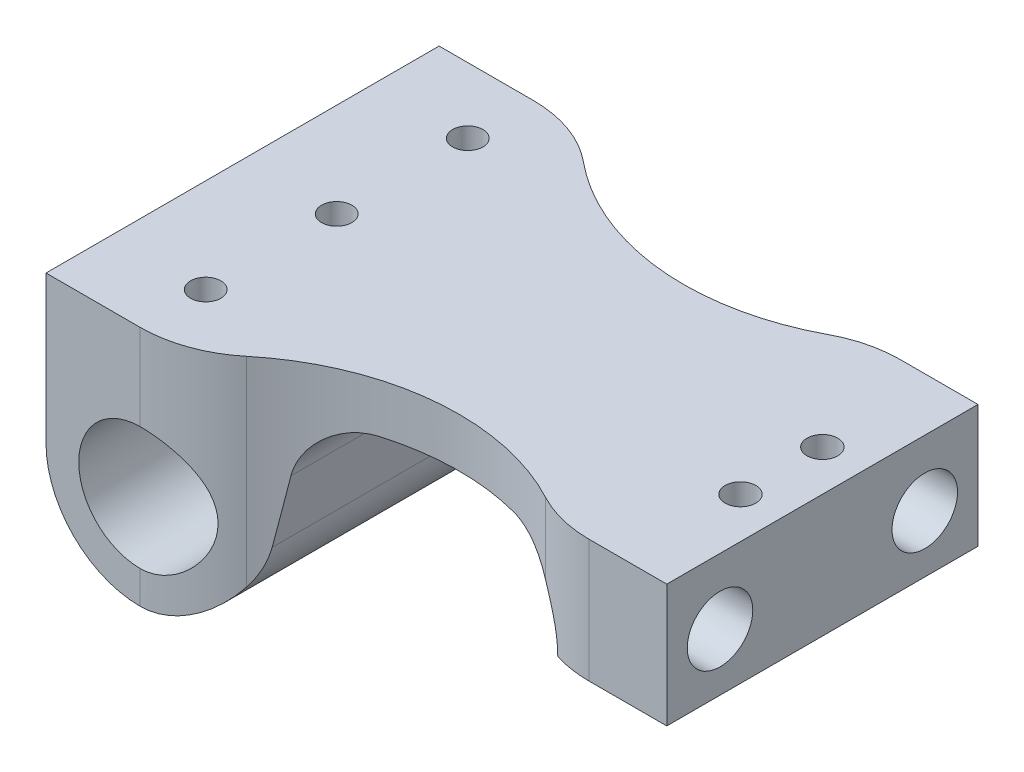
SolidWorks part; units mm, degrees
ref_plane "Front Plane" through (0, 0, 0) normal (0, 0, 1) x (1, 0, 0)
ref_plane "Top Plane" through (0, 0, 0) normal (0, 1, 0) x (1, 0, 0)
ref_plane "Right Plane" through (0, 0, 0) normal (1, 0, 0) x (0, 0, -1)
sketch "Sketch1" plane through (0, 0, 0) normal (0, 0, 1) x (1, 0, 0)
  line L0 (-17.4747, 5.003) -> (-16.0995, 12.8024)
  line L1 (10, -10) -> (-10, -10) construction
  line L2 (10, -10) -> (10, 10) construction
  line L3 (10, 10) -> (-10, 10) construction
  line L4 (-10, -10) -> (-10, 10) construction
  line L5 (10, -10) -> (-10, 10) construction
  line L6 (10, 10) -> (-10, -10) construction
  line L7 (10, 10) -> (20, 10) construction
  line L8 (10, 10) -> (10, -10) construction
  line L9 (10, -10) -> (20, -10) construction
  line L10 (20, 10) -> (20, -10) construction
  line L11 (-10, 10) -> (10, 10) construction
  line L12 (-10, 10) -> (-10, 19) construction
  line L13 (-10, 19) -> (10, 19) construction
  line L14 (10, 10) -> (10, 19) construction
  line L15 (-10, 10) -> (10, 10) construction
  line L16 (-10, 10) -> (-10, 15) construction
  line L17 (-10, 15) -> (10, 15) construction
  line L18 (10, 10) -> (10, 15) construction
  line L19 (16.5, 14.5) -> (36.5, 14.5) construction
  line L20 (16.5, 14.5) -> (16.5, 10) construction
  line L21 (25, -0.5) -> (36.5, -0.5) construction
  line L22 (36.5, 14.5) -> (36.5, -0.5) construction
  line L23 (-40.3, 25) -> (12.6275, 25)
  line L24 (-40.3, 25) -> (-40.3, 7)
  line L25 (-8.7134, 19) -> (7.5, 19)
  line L28 (25, 10) -> (25, 25)
  line L29 (25, 25) -> (12.6275, 25)
  line L30 (16.5, 10) -> (25, 10)
  line L31 (-10, 15) -> (-15, 15) construction
  line L32 (-10, 15) -> (-10, -4.1558) construction
  line L33 (-10, -4.1558) -> (-15, -4.1558) construction
  line L34 (-15, 15) -> (-15, -4.1558) construction
  circle A0 centre (-28.8, 7) radius 7.5
  arc A1 (-40.3, 7) -> (-17.4747, 5.003) centre (-28.8, 7) ccw
  arc A2 (-16.0995, 12.8024) -> (-8.7134, 19) centre (-8.7134, 11.5) cw
  arc A3 (7.5, 19) -> (16.5, 10) centre (7.5, 10) cw
  point P3 (0, 0)
  dimension "D1" = 15
  dimension "D2" = 4
  dimension "D5" = 18.8
  dimension "D6" = 3
  dimension "D10" = 6.5
  dimension "D13" = 7.5
  dimension "D3" = 20
  dimension "D4" = 20
  dimension "D7" = 10
  dimension "D8" = 9
  dimension "D9" = 5
  dimension "D11" = 20
  dimension "D12" = 6
  dimension "D14" = 80
  dimension "D15" = 5
  dimension "D16" = 5
extrude "Boss-Extrude1" add sketch "Sketch1" along normal mid plane 48
sketch "Sketch2" plane through (25, 0, 0) normal (1, 0, 0) x (0, 0, -1)
  line L0 (-12.5, 17) -> (0, 0) construction
  line L1 (0, 0) -> (12.5, 17) construction
  line L3 (-24, 25) -> (24, 25) construction
  circle A0 centre (-12.5, 17) radius 4
  circle A1 centre (12.5, 17) radius 4
  dimension "D1" = 8
  dimension "D2" = 25
  dimension "D3" = 8
extrude "Cut-Extrude1" cut sketch "Sketch2" against normal blind 5
sketch "Sketch3" plane through (0, 25, 0) normal (0, 1, 0) x (1, 0, 0)
  line L0 (25, -24) -> (-40.3, -24) construction
  line L1 (-28.8, -24) -> (25, -24)
  line L2 (25, -24) -> (25, -19)
  line L3 (21, -19) -> (25, -19)
  line L4 (25, -24) -> (25, 24) construction
  line L5 (-36.3, -24) -> (-21.3, -24) construction
  line L6 (0, 0) -> (25, 0) construction
  line L7 (21, 19) -> (25, 19)
  line L8 (25, 24) -> (25, 19)
  line L9 (-28.8, 24) -> (25, 24)
  arc A0 (-19.2546, -20.5709) -> (13.9454, -17.2375) centre (-0.1638, -43.7126) cw
  arc A1 (-28.8, -24) -> (-19.2546, -20.5709) centre (-28.8, -9) ccw
  arc A2 (13.9454, -17.2375) -> (21, -19) centre (21, -4) ccw
  arc A3 (13.9454, 17.2375) -> (21, 19) centre (21, 4) cw
  arc A4 (-28.8, 24) -> (-19.2546, 20.5709) centre (-28.8, 9) cw
  arc A5 (-19.2546, 20.5709) -> (13.9454, 17.2375) centre (-0.1638, 43.7126) ccw
  dimension "D2" = 15
  dimension "D3" = 30
  dimension "D4" = 15
  dimension "D1" = 5
  dimension "D5" = 4
extrude "Cut-Extrude2" cut sketch "Sketch3" against normal through all both and the other way through all
sketch "Sketch4" plane through (25, 0, 0) normal (1, 0, 0) x (0, 0, -1)
  line L1 (-19, 25) -> (19, 25)
  line L2 (-19, 25) -> (-19, 10)
  line L3 (-19, 10) -> (19, 10)
  line L4 (19, 25) -> (19, 10)
  circle A0 centre (12.5, 17) radius 4 construction
  circle A1 centre (-12.5, 17) radius 4 construction
  circle A2 centre (12.5, 17) radius 4
  circle A3 centre (-12.5, 17) radius 4
extrude "Boss-Extrude2" add sketch "Sketch4" along normal blind 5.5
sketch "Sketch5" plane through (0, 25, 0) normal (0, 1, 0) x (1, 0, 0)
  line L0 (30.5, 19) -> (25.5, 5) construction
  line L1 (25.5, 5) -> (25.5, -5) construction
  line L2 (25.5, -5) -> (30.5, -19) construction
  line L3 (30.5, 19) -> (30.5, -19) construction
  circle A0 centre (25.5, -5) radius 1.875
  circle A1 centre (25.5, 5) radius 1.875
  dimension "D1" = 3.75
  dimension "D2" = 3.75
  dimension "D3" = 10
  dimension "D4" = 5
extrude "Cut-Extrude3" cut sketch "Sketch5" against normal through all both and the other way through all
sketch "Sketch6" plane through (0, 25, 0) normal (0, 1, 0) x (1, 0, 0)
  line L0 (-28.8, -24) -> (-28.8, 24) construction
  line L1 (-28.8, 16) -> (-40.3, 24) construction
  line L2 (-40.3, 24) -> (-40.3, -24) construction
  line L3 (-40.3, -24) -> (-28.8, -16) construction
  line L4 (-28.8, 24) -> (-40.3, 24) construction
  circle A0 centre (-28.8, 16) radius 1.85
  circle A1 centre (-28.8, 0) radius 1.85
  circle A2 centre (-28.8, -16) radius 1.85
  arc A3 (-28.8, -24) -> (-19.2546, -20.5709) centre (-28.8, -9) ccw construction
  point P13 (0, 0)
  point P15 (0, 0)
  dimension "D1" = 3.7
  dimension "D2" = 8
extrude "Cut-Extrude4" cut sketch "Sketch6" against normal blind 9
